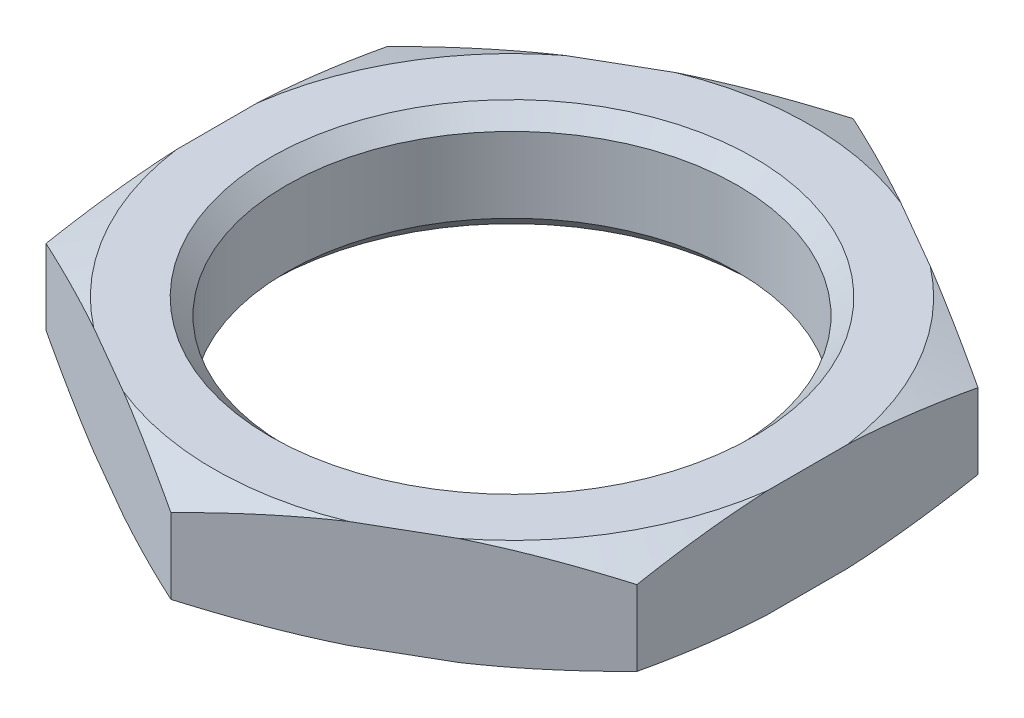
SolidWorks part; units mm, degrees
ref_plane "Front Plane" through (0, 0, 0) normal (0, 0, 1) x (1, 0, 0)
ref_plane "Top Plane" through (0, 0, 0) normal (0, 1, 0) x (1, 0, 0)
ref_plane "Right Plane" through (0, 0, 0) normal (1, 0, 0) x (0, 0, -1)
sketch "Sketch1" plane through (0, 0, 0) normal (0, 1, 0) x (1, 0, 0)
  line L1 (0, 6.3509) -> (-5.5, 3.1754)
  line L2 (-5.5, 3.1754) -> (-5.5, -3.1754)
  line L3 (-5.5, -3.1754) -> (0, -6.3509)
  line L4 (0, -6.3509) -> (5.5, -3.1754)
  line L5 (5.5, -3.1754) -> (5.5, 3.1754)
  line L6 (5.5, 3.1754) -> (0, 6.3509)
  circle A0 centre (0, 0) radius 5.5 construction
  circle A1 centre (0, 0) radius 4.2
  dimension "D2" = 8.4
  dimension "D1" = 11
extrude "Boss-Extrude1" add sketch "Sketch1" along normal blind 2
chamfer "Chamfer1" distance 0.3 angle 45 2 edges at (0, 0, 4.2) (0, 2, 4.2)
sketch "Sketch3" plane through (0, 0, 0) normal (1, 0, 0) x (0, 0, -1)
  line L0 (-6.3509, 0) -> (-5.5509, 0)
  line L1 (-6.3509, 0) -> (-3.1754, 0) construction
  line L2 (-5.5509, 0) -> (-6.3509, 0.3)
  line L3 (-6.3509, 2) -> (-6.3509, 0) construction
  line L4 (-6.3509, 0.3) -> (-6.3509, 0)
  line L5 (-6.3509, 2) -> (-6.3509, 1.7)
  line L6 (-6.3509, 1.7) -> (-5.5509, 2)
  line L7 (-6.3509, 2) -> (-3.1754, 2) construction
  line L8 (-5.5509, 2) -> (-6.3509, 2)
  line L9 (0, 0) -> (0, 2) construction
  line L10 (-3.1754, 0) -> (3.1754, 0) construction
  line L11 (-3.1754, 2) -> (3.1754, 2) construction
  dimension "D1" = 0.8
  dimension "D2" = 0.3
revolve "Cut-Revolve1" cut sketch "Sketch3" angle 360 about L9
